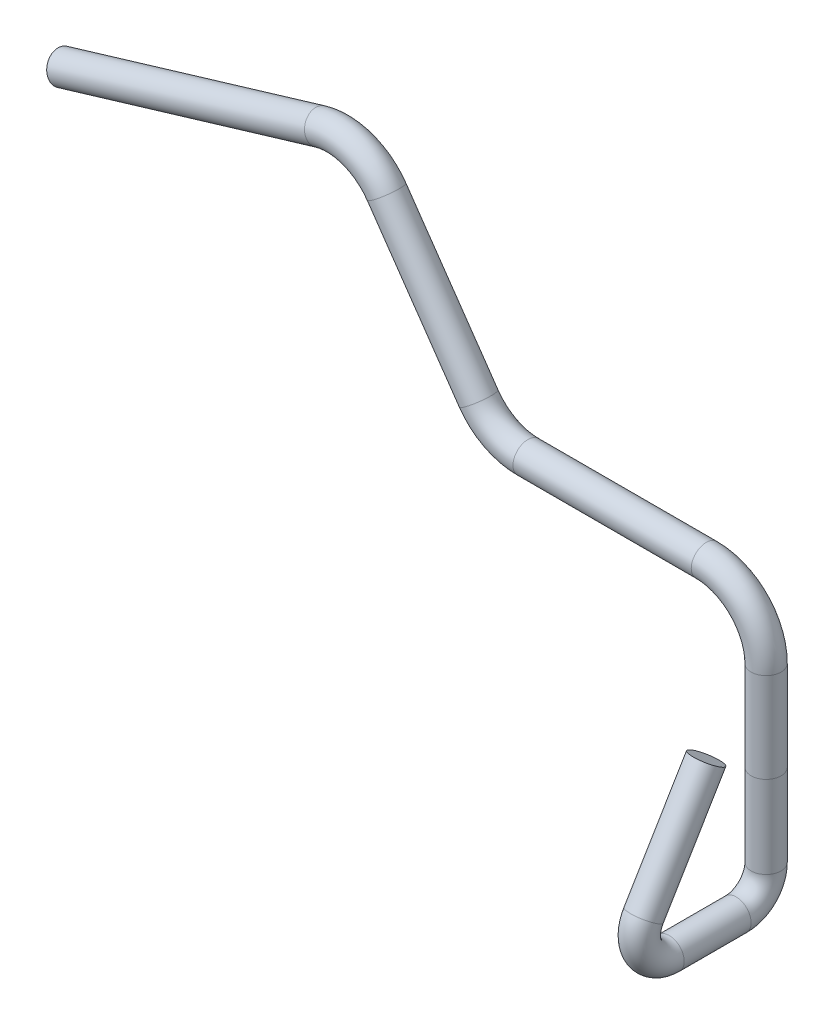
SolidWorks part; units mm, degrees
material "Plain Carbon Steel"
ref_plane "Front Plane" through (0, 0, 0) normal (0, 0, 1) x (1, 0, 0)
ref_plane "Top Plane" through (0, 0, 0) normal (0, 1, 0) x (1, 0, 0)
ref_plane "Right Plane" through (0, 0, 0) normal (1, 0, 0) x (0, 0, -1)
sketch "Sketch1" plane through (0, 0, 0) normal (0, 0, 1) x (1, 0, 0)
  line L0 (0, 0) -> (0, 15.24)
  line L1 (-10.16, 25.4) -> (-40.3966, 25.4)
  line L2 (-48.7501, 29.7768) -> (-64.378, 52.3504)
  line L3 (-75.6509, 56.2987) -> (-119.38, 43.18)
  arc A0 (0, 15.24) -> (-10.16, 25.4) centre (-10.16, 15.24) ccw
  arc A1 (-40.3966, 25.4) -> (-48.7501, 29.7768) centre (-40.3966, 35.56) cw
  arc A2 (-64.378, 52.3504) -> (-75.6509, 56.2987) centre (-72.7314, 46.5672) ccw
  point P8 (0, 25.4)
  point P11 (-45.72, 25.4)
  point P14 (-68.58, 58.42)
  dimension "D7" = 10.16
  dimension "D1" = 25.4
  dimension "D2" = 45.72
  dimension "D3" = 50.8
  dimension "D4" = 22.86
  dimension "D5" = 15.24
  dimension "D6" = 33.02
sketch "Sketch2" plane through (0, 0, 0) normal (1, 0, 0) x (0, 0, -1)
  line L0 (0, 0) -> (0, -13.97)
  line L1 (-5.08, -19.05) -> (-16.4278, -19.05)
  line L2 (-20.7838, -11.3564) -> (-10.16, 6.35)
  arc A0 (0, -13.97) -> (-5.08, -19.05) centre (-5.08, -13.97) cw
  arc A1 (-16.4278, -19.05) -> (-20.7838, -11.3564) centre (-16.4278, -13.97) cw
  point P8 (0, -19.05)
  point P11 (-25.4, -19.05)
  dimension "D5" = 5.08
  dimension "D1" = 19.05
  dimension "D2" = 25.4
  dimension "D3" = 25.4
  dimension "D4" = 15.24
curve "CompCurve1"
sweep "Sweep1" add path "CompCurve1" circular profile diameter 5.08 parameters "D3"=5.08
